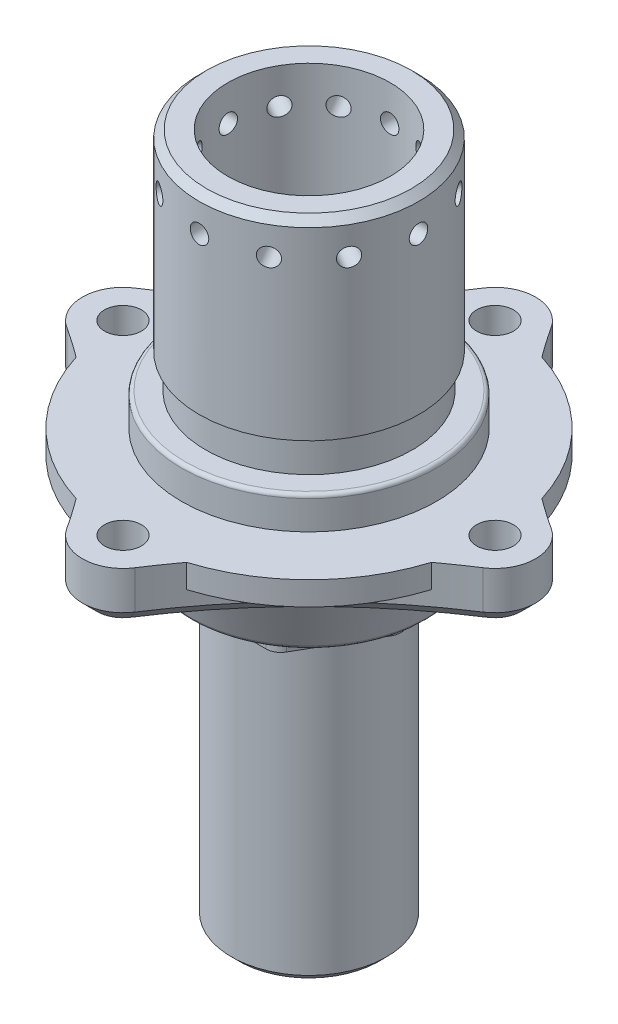
SolidWorks part; units mm, degrees
material "7075-T6 (SN)"
ref_plane "X-Y Datum" through (0, 0, 0) normal (0, 0, 1) x (1, 0, 0)
ref_plane "X-Z Datum" through (0, 0, 0) normal (0, 1, 0) x (1, 0, 0)
ref_plane "Y-Z Datum" through (0, 0, 0) normal (1, 0, 0) x (0, 0, -1)
sketch "Sketch1" plane through (0, 0, 0) normal (1, 0, 0) x (0, 0, -1)
  line L0 (0, 0) -> (-50000, 0) construction
  line L1 (0, 0) -> (0, 50000) construction
  line L2 (0, 0) -> (-29.4793, 0)
  line L3 (-29.4793, 0) -> (-25.0825, -12.0802)
  line L4 (-25.0825, -12.0802) -> (-25.0825, -16.8427)
  line L5 (-25.0825, -16.8427) -> (-16.6688, -16.8427)
  line L8 (0, -80.3427) -> (0, 0)
  line L9 (0, -80.3427) -> (-15.0813, -80.3427)
  line L10 (-16.6688, -16.8427) -> (-16.6687, -78.7552)
  line L11 (-15.0813, -80.3427) -> (-16.6687, -78.7552)
  dimension "D1" = 80.3427
  dimension "D2" = 4.7625
  dimension "D3" = 63.5
  dimension "D4" = 50.165
  dimension "D5" = 45
  dimension "D6" = 70
  dimension "D7" = 33.3375
  dimension "D8" = 1.5875
sketch "Sketch2" plane through (0, 0, 0) normal (1, 0, 0) x (0, 0, -1)
  line L0 (0, 0) -> (-52.3875, 0)
  line L1 (200000, 0) -> (-250000, 0) construction
  line L2 (-52.3875, 0) -> (-52.3875, 11.43)
  line L3 (-52.3875, 11.43) -> (-27.4096, 11.43)
  line L4 (-27.4096, 11.43) -> (-27.4096, 18.43)
  line L5 (-27.4096, 18.43) -> (-22.225, 18.43)
  line L6 (-22.225, 18.43) -> (-22.225, 25.7175)
  line L7 (-22.225, 25.7175) -> (-23.6195, 25.7175)
  line L10 (0, -200000) -> (0, 250000) construction
  line L11 (0, 66.9925) -> (0, 0)
  line L15 (0, 66.9925) -> (-22.032, 66.9925)
  line L16 (-22.032, 66.9925) -> (-23.6195, 65.405)
  line L17 (-23.6195, 65.405) -> (-23.6195, 25.7175)
  line L18 (0, 0) -> (-50000, 0) construction
  line L19 (0, 0) -> (0, 50000) construction
  line L20 (0, 0) -> (0, -31242.0183) construction
  dimension "D1" = 11.43
  dimension "D2" = 55.5625
  dimension "D3" = 47.2389
  dimension "D4" = 1.5875
  dimension "D5" = 45
  dimension "D6" = 54.8192
  dimension "D7" = 104.775
  dimension "D8" = 7
  dimension "D9" = 39.6875
  dimension "D10" = 44.45
revolve "Bearing Shaft/Flange Support" add sketch "Sketch1" angle 360 about L1
revolve "Drive Pin Support" add sketch "Sketch2" angle 360 about L19
sketch "Sketch5" plane through (0, 0, 0) normal (1, 0, 0) x (0, 0, -1)
  line L0 (0, 66.9925) -> (17.4625, 66.9925)
  line L1 (22.032, 66.9925) -> (-22.032, 66.9925) construction
  line L2 (17.4625, 66.9925) -> (17.4625, 19.3675)
  line L3 (17.4625, 19.3675) -> (12.7, -12.3825)
  line L4 (12.7, -12.3825) -> (0, -12.3825)
  line L5 (0, -12.3825) -> (0, 66.9925)
  line L6 (0, 0) -> (-50000, 0) construction
  line L8 (0, 0) -> (0, -50000) construction
  dimension "D1" = 79.375
  dimension "D2" = 47.625
  dimension "D3" = 34.925
  dimension "D4" = 25.4
revolve "Center Mass Removal" cut sketch "Sketch5" angle 360 about L8
hole_wizard "Drive Pin Holes" positions "Sketch6" profile "Sketch7" tap size "3/8-16" standard "ANSI Inch" end condition through all
sketch "Sketch6" plane through (0, 0, 0) normal (0, -1, 0) x (-1, 0, 0)
  circle A0 centre (0, 0) radius 40 construction
  point P0 (0, -40)
  dimension "D1" = 80
sketch "Sketch7" plane through (0, 0, 40) normal (1, 0, 0) x (0, 0, -1)
  line L0 (0, 0) -> (0, 66.9925)
  line L1 (0, 66.9925) -> (3.9687, 66.9925)
  line L2 (3.9687, 66.9925) -> (3.9687, 0)
  line L5 (3.9687, 0) -> (0, 0)
  line L11 (0, -6.35) -> (0, 107.95) construction
  dimension "Thru Tap Drill Dia." = 7.9375
  dimension "Thru Tap Drill Depth" = 66.9925
cosmetic thread "Hole Thread1" parameters "D2"=9.525
pattern_circular "Drive Pin Holes Pattern" count 4 over 360 about axis through (0, 0, 0) along (0, 1, 0) of "Drive Pin Holes"
cosmetic thread "Hole Thread2" parameters "D2"=9.525
cosmetic thread "Hole Thread3" parameters "D2"=9.525
cosmetic thread "Hole Thread4" parameters "D2"=9.525
sketch "Sketch8" plane through (0, 0, 0) normal (0, -1, 0) x (1, 0, 0)
  arc A0 (7.3249, 44.7518) -> (-7.3249, 44.7518) centre (0, 40) ccw
  arc A1 (7.3249, 44.7518) -> (44.7518, 7.3249) centre (113.8695, 113.8695) ccw
  arc A2 (44.7518, -7.3249) -> (44.7518, 7.3249) centre (40, 0) ccw
  arc A3 (44.7518, -7.3249) -> (44.7518, 7.3249) centre (40, 0) ccw
  arc A5 (44.7518, -7.3249) -> (7.3249, -44.7518) centre (113.8695, -113.8695) ccw
  circle A7 centre (0, 40) radius 3.9687 construction
  circle A8 centre (0, 0) radius 52.3875 construction
  circle A9 centre (0, 0) radius 40 construction
  arc A10 (-7.3249, -44.7518) -> (7.3249, -44.7518) centre (0, -40) ccw
  arc A11 (-7.3249, -44.7518) -> (7.3249, -44.7518) centre (0, -40) ccw
  arc A13 (-44.7518, 7.3249) -> (-44.7518, -7.3249) centre (-40, 0) ccw
  arc A14 (-44.7518, 7.3249) -> (-44.7518, -7.3249) centre (-40, 0) ccw
  arc A15 (-44.7518, 7.3249) -> (-7.3249, 44.7518) centre (-113.8695, 113.8695) ccw
  arc A16 (7.3249, 44.7518) -> (-7.3249, 44.7518) centre (0, 40) ccw
  circle A17 centre (0, 0) radius 52.3875
  arc A18 (-7.3249, -44.7518) -> (-44.7518, -7.3249) centre (-113.8695, -113.8695) ccw
  arc A19 (-170.1077, 0) -> (0, -170.1077) centre (-113.8695, -113.8695) ccw [skipped]
  circle M10 centre (0, 0) radius 52.3875
  dimension "D1" = 4.7625
  dimension "D3" = 254
  dimension "D4" = 80
  dimension "D5" = 4
extrude "Flange Support Cut" cut sketch "Sketch8" against normal blind 6.35 contours A10 A18 A13 A15 A0 A1 A2 A5 M10
sketch "Sketch9" plane through (0, 6.35, 0) normal (0, -1, 0) x (1, 0, 0)
  line L0 (0, 0) -> (0, 50000) construction
  line L1 (0, 0) -> (50000, 0) construction
  line L2 (0, 0) -> (-35355.3391, 35355.3391) construction
  arc A0 (-44.7518, 7.3249) -> (-44.7518, -7.3249) centre (-40, 0) ccw construction
  arc A1 (-7.3249, -44.7518) -> (-44.7518, -7.3249) centre (-113.8695, -113.8695) ccw construction
  arc A2 (-7.3249, -44.7518) -> (7.3249, -44.7518) centre (0, -40) ccw construction
  arc A3 (44.7518, -7.3249) -> (7.3249, -44.7518) centre (113.8695, -113.8695) ccw construction
  arc A4 (44.7518, -7.3249) -> (44.7518, 7.3249) centre (40, 0) ccw construction
  arc A5 (7.3249, 44.7518) -> (44.7518, 7.3249) centre (113.8695, 113.8695) ccw construction
  arc A6 (7.3249, 44.7518) -> (-7.3249, 44.7518) centre (0, 40) ccw construction
  arc A7 (-44.7518, 7.3249) -> (-7.3249, 44.7518) centre (-113.8695, 113.8695) ccw construction
  arc A8 (-44.7518, 7.3249) -> (-44.7518, -7.3249) centre (-40, 0) ccw
  arc A9 (-7.3249, -44.7518) -> (-11.8767, -38.1961) centre (-113.8695, -113.8695) ccw
  arc A10 (-7.3249, -44.7518) -> (7.3249, -44.7518) centre (0, -40) ccw
  arc A11 (44.7518, -7.3249) -> (38.1961, -11.8767) centre (113.8695, -113.8695) ccw
  arc A12 (44.7518, -7.3249) -> (44.7518, 7.3249) centre (40, 0) ccw
  arc A13 (7.3249, 44.7518) -> (11.8767, 38.1961) centre (113.8695, 113.8695) ccw
  arc A14 (7.3249, 44.7518) -> (-7.3249, 44.7518) centre (0, 40) ccw
  arc A15 (-44.7518, 7.3249) -> (-38.1961, 11.8767) centre (-113.8695, 113.8695) ccw
  arc A20 (38.1961, 11.8767) -> (44.7518, 7.3249) centre (113.8695, 113.8695) ccw
  arc A21 (-11.8767, 38.1961) -> (-7.3249, 44.7518) centre (-113.8695, 113.8695) ccw
  arc A22 (11.8767, -38.1961) -> (7.3249, -44.7518) centre (113.8695, -113.8695) ccw
  arc A23 (-38.1961, -11.8767) -> (-44.7518, -7.3249) centre (-113.8695, -113.8695) ccw
  circle A24 centre (0, 0) radius 40 construction
  circle A25 centre (0, 0) radius 40
  dimension "D1" = 45
extrude "Floral Pattern Cut" cut sketch "Sketch9" against normal through all
sketch "Sketch10" plane through (0, -16.8427, 0) normal (0, -1, 0) x (1, 0, 0)
  line L0 (0, 0) -> (0, 50000) construction
  line L1 (10.1025, -17.4981) -> (20.205, 0)
  line L2 (20.205, 0) -> (10.1025, 17.4981)
  line L3 (10.1025, 17.4981) -> (-10.1025, 17.4981)
  line L4 (-10.1025, 17.4981) -> (-20.205, 0)
  line L5 (-20.205, 0) -> (-10.1025, -17.4981)
  line L6 (-10.1025, -17.4981) -> (10.1025, -17.4981)
  line L7 (0, 0) -> (50000, 0) construction
  circle A0 centre (0, 0) radius 17.4981 construction
  circle A1 centre (0, 0) radius 25.0825 construction
  circle A2 centre (0, 0) radius 25.0825
  point P17 (0, 17.4981)
  dimension "D1" = 34.9961
extrude "Brake Hat Hex" cut sketch "Sketch10" against normal blind 4.7625
sketch "Sketch11" plane through (0, -80.3427, 0) normal (0, -1, 0) x (1, 0, 0)
  circle A25 centre (0, 0) radius 9.525 construction
  circle A26 centre (0, 9.525) radius 3.175
  circle A27 centre (8.2489, 4.7625) radius 3.175
  circle A28 centre (8.2489, -4.7625) radius 3.175
  circle A29 centre (0, -9.525) radius 3.175
  circle A30 centre (-8.2489, -4.7625) radius 3.175
  circle A31 centre (-8.2489, 4.7625) radius 3.175
  dimension "D1" = 19.05
  dimension "D2" = 6.35
  dimension "D3" = 6
hole_wizard "5/16 Clearance Hole1" positions "Sketch12" profile "Sketch13" hole size "5/16" standard "ANSI Inch" end condition through all
sketch "Sketch12" plane through (0, -80.3427, 0) normal (0, -1, 0) x (-1, 0, 0)
  point P0 (0, 0)
sketch "Sketch13" plane through (0, -80.3427, 0) normal (1, 0, 0) x (0, 0, -1)
  line L0 (0, 0) -> (0, 147.3352)
  line L1 (0, 147.3352) -> (4.1021, 147.3352)
  line L2 (4.1021, 147.3352) -> (4.1021, 0)
  line L5 (4.1021, 0) -> (0, 0)
  line L11 (0, -6.35) -> (0, 107.95) construction
  dimension "Thru Hole Dia." = 8.2042
  dimension "Thru Hole Depth" = 147.3352
fillet "Brake Hat Fillet" radius 3.175 6 edges at (20.205, -14.4615, 0) (10.1025, -14.4615, 17.4981) (-10.1025, -14.4615, 17.4981) (-20.205, -14.4615, 0) (-10.1025, -14.4615, -17.4981) (10.1025, -14.4615, -17.4981)
fillet "Hub Fillet" radius 0.7937 1 edges at (0, 18.43, -27.4096)
sketch "Sketch14" plane through (0, 0, 0) normal (1, 0, 0) x (0, 0, -1)
  line L0 (17.4625, 66.9925) -> (-17.4625, 66.9925) construction
  line L1 (0, 0) -> (-50000, 0) construction
  line L2 (0, 0) -> (0, -50000) construction
  circle A0 centre (0, 59.3725) radius 1.9844
  dimension "D2" = 3.9688
  dimension "D1" = 7.62
extrude "Pin Holes" cut sketch "Sketch14" against normal through all
pattern_circular "Pin Hole Pattern" count 12 over 360 about axis through (0, 66.9925, 0) along (0, 1, 0) of "Pin Holes"
chamfer "Floral Pattern Chamfer" distance 3.175 angle 45 8 edges at (0, 0, -48.7312) (24.067, 0, -24.067) (48.7312, 0, 0) (-24.067, 0, -24.067) (-48.7312, 0, 0) (-24.067, 0, 24.067) (0, 0, 48.7313) (24.067, 0, 24.067)
fillet "Floral Pattern Fillet" [suppressed] radius 6.35
sketch3d "3DSketch2"
  line L0 (0, 0, 0) -> (0, 0, -205.74)
  line L1 (0, 0, -205.74) -> (25.4, 0, -205.74)
  line L2 (0, 0, -205.74) -> (0, -25.4, -205.74)
  dimension "D1" = 25.4
  dimension "D2" = 25.4
  dimension "D3" = 205.74
extrude "Tripod Pins" [suppressed] cut sketch "Sketch11" against normal blind 12.7
fillet "Flange Fillet" radius 1.27 1 edges at (0, -12.0802, -25.0825)
sketch "Sketch15" plane through (0, 0, 0) normal (0, -1, 0) x (1, 0, 0)
  circle A0 centre (0, 0) radius 40 construction
  dimension "D1" = 80
thread "Thread1" [suppressed] pitch 2.1167 start angle 0, offset 0.3048, length 0, pitch 2.1167, diameter 47.625
ref_plane "Plane1" through (-23.8125, 67.2973, 0) normal (0, 0, 1) x (-1, 0, 0)
sketch "Thread Profile1" plane through (-23.8125, 67.2973, 0) normal (0, 0, 1) x (-1, 0, 0)
  line L0 (0, 0) -> (0, 2.1167) construction
  line L11 (0, 0) -> (0, 1.8521)
  line L12 (0, 1.8521) -> (-1.1457, 1.1906)
  line L13 (-1.1457, 1.1906) -> (-1.1457, 0.6615)
  line L15 (-1.1457, 0.6615) -> (0, 0)
  line L17 (-1.1457, 0.926) -> (0, 0.926) construction
  point P2 (0, 0)
  dimension "Pitch" = 2.1167
  dimension "Profile_Angle" = 60
  dimension "Profile_Land" = 0.5292
  dimension "Profile_Height" = 1.1457
sketch "Sketch16" plane through (0, -80.3427, 0) normal (0, -1, 0) x (1, 0, 0)
  line L1 (0, 0) -> (0, 50000) construction
  line L20 (-2.921, 9.5113) -> (-2.921, 8.1525)
  line L21 (2.921, 9.5113) -> (2.921, 8.1525)
  line L36 (4.66, 8.7909) -> (3.6992, 7.8302)
  line L37 (8.7909, 4.66) -> (7.8302, 3.6992)
  line L38 (9.5113, 2.921) -> (8.1525, 2.921)
  line L39 (9.5113, -2.921) -> (8.1525, -2.921)
  line L61 (8.7909, -4.66) -> (7.8302, -3.6992)
  line L62 (4.66, -8.7909) -> (3.6992, -7.8302)
  line L63 (2.921, -9.5113) -> (2.921, -8.1525)
  line L64 (-2.921, -9.5113) -> (-2.921, -8.1525)
  line L65 (-4.66, -8.7909) -> (-3.6992, -7.8302)
  line L66 (-8.7909, -4.66) -> (-7.8302, -3.6992)
  line L67 (-9.5113, -2.921) -> (-8.1525, -2.921)
  line L68 (-9.5113, 2.921) -> (-8.1525, 2.921)
  line L69 (-8.7909, 4.66) -> (-7.8302, 3.6992)
  line L70 (-4.66, 8.7909) -> (-3.6992, 7.8302)
  circle A1 centre (0, 0) radius 15.0813
  circle A2 centre (0, 0) radius 15.0813 construction
  arc A3 (-5.0106, 8.8385) -> (-8.8385, 5.0106) centre (0, 0) ccw
  arc A24 (-7.8302, 3.6992) -> (-8.1525, 2.921) centre (0, 0) ccw
  arc A25 (2.7067, 9.7928) -> (-2.7067, 9.7928) centre (0, 0) ccw
  arc A26 (8.8385, 5.0106) -> (5.0106, 8.8385) centre (0, 0) ccw
  arc A27 (9.7928, -2.7067) -> (9.7928, 2.7067) centre (0, 0) ccw
  arc A28 (5.0106, -8.8385) -> (8.8385, -5.0106) centre (0, 0) ccw
  arc A29 (-2.7067, -9.7928) -> (2.7067, -9.7928) centre (0, 0) ccw
  arc A30 (-8.8385, -5.0106) -> (-5.0106, -8.8385) centre (0, 0) ccw
  arc A31 (-9.7928, 2.7067) -> (-9.7928, -2.7067) centre (0, 0) ccw
  arc A32 (-2.921, 8.1525) -> (-3.6992, 7.8302) centre (0, 0) ccw
  arc A33 (3.6992, 7.8302) -> (2.921, 8.1525) centre (0, 0) ccw
  arc A34 (8.1525, 2.921) -> (7.8302, 3.6992) centre (0, 0) ccw
  arc A35 (7.8302, -3.6992) -> (8.1525, -2.921) centre (0, 0) ccw
  arc A36 (2.921, -8.1525) -> (3.6992, -7.8302) centre (0, 0) ccw
  arc A37 (-3.6992, -7.8302) -> (-2.921, -8.1525) centre (0, 0) ccw
  arc A38 (-8.1525, -2.921) -> (-7.8302, -3.6992) centre (0, 0) ccw
  arc A39 (-2.921, 9.5113) -> (-2.7067, 9.7928) centre (-2.6289, 9.5113) cw
  arc A40 (2.921, 9.5113) -> (2.7067, 9.7928) centre (2.6289, 9.5113) ccw
  arc A41 (4.66, 8.7909) -> (5.0106, 8.8385) centre (4.8666, 8.5844) cw
  arc A42 (8.7909, 4.66) -> (8.8385, 5.0106) centre (8.5844, 4.8666) ccw
  arc A43 (9.5113, 2.921) -> (9.7928, 2.7067) centre (9.5113, 2.6289) cw
  arc A85 (9.5113, -2.921) -> (9.7928, -2.7067) centre (9.5113, -2.6289) ccw
  arc A86 (8.7909, -4.66) -> (8.8385, -5.0106) centre (8.5844, -4.8666) cw
  arc A87 (4.66, -8.7909) -> (5.0106, -8.8385) centre (4.8666, -8.5844) ccw
  arc A88 (2.921, -9.5113) -> (2.7067, -9.7928) centre (2.6289, -9.5113) cw
  arc A89 (-2.921, -9.5113) -> (-2.7067, -9.7928) centre (-2.6289, -9.5113) ccw
  arc A90 (-4.66, -8.7909) -> (-5.0106, -8.8385) centre (-4.8666, -8.5844) cw
  arc A91 (-8.7909, -4.66) -> (-8.8385, -5.0106) centre (-8.5844, -4.8666) ccw
  arc A92 (-9.5113, -2.921) -> (-9.7928, -2.7067) centre (-9.5113, -2.6289) cw
  arc A93 (-9.5113, 2.921) -> (-9.7928, 2.7067) centre (-9.5113, 2.6289) ccw
  arc A94 (-8.7909, 4.66) -> (-8.8385, 5.0106) centre (-8.5844, 4.8666) cw
  arc A95 (-4.66, 8.7909) -> (-5.0106, 8.8385) centre (-4.8666, 8.5844) ccw
  point P40 (0, 0)
  point P101 (0, 0)
  dimension "D2" = 20.32
  dimension "D3" = 17.32
  dimension "D5" = 0.2921
  dimension "D4" = 5.842
  dimension "D1" = 0
  dimension "D6" = 8
extrude "Cut-Extrude1" cut sketch "Sketch16" against normal blind 19.05
equation "\"SplineDO\"= 0.8in'Outer diameter of spline"
equation "\"TeethNumber\"= 10'number of spline teeth"
equation "\"D2@Sketch16\"= \"SplineDO\""
equation "\"D3@Sketch16\"= ( ( \"SplineDO\" * 25.4 ) - 3 ) / 25.4"
equation "\"TeethWidth\"=0.230000"
equation "\"D4@Sketch16\"= \"TeethWidth\""
equation "\"D5@Sketch16\" = \"TeethWidth\" * 0.05"
equation "\"SplineDepth\"=0.750000"
equation "\"D1@Cut-Extrude1\"=\"SplineDepth\""
